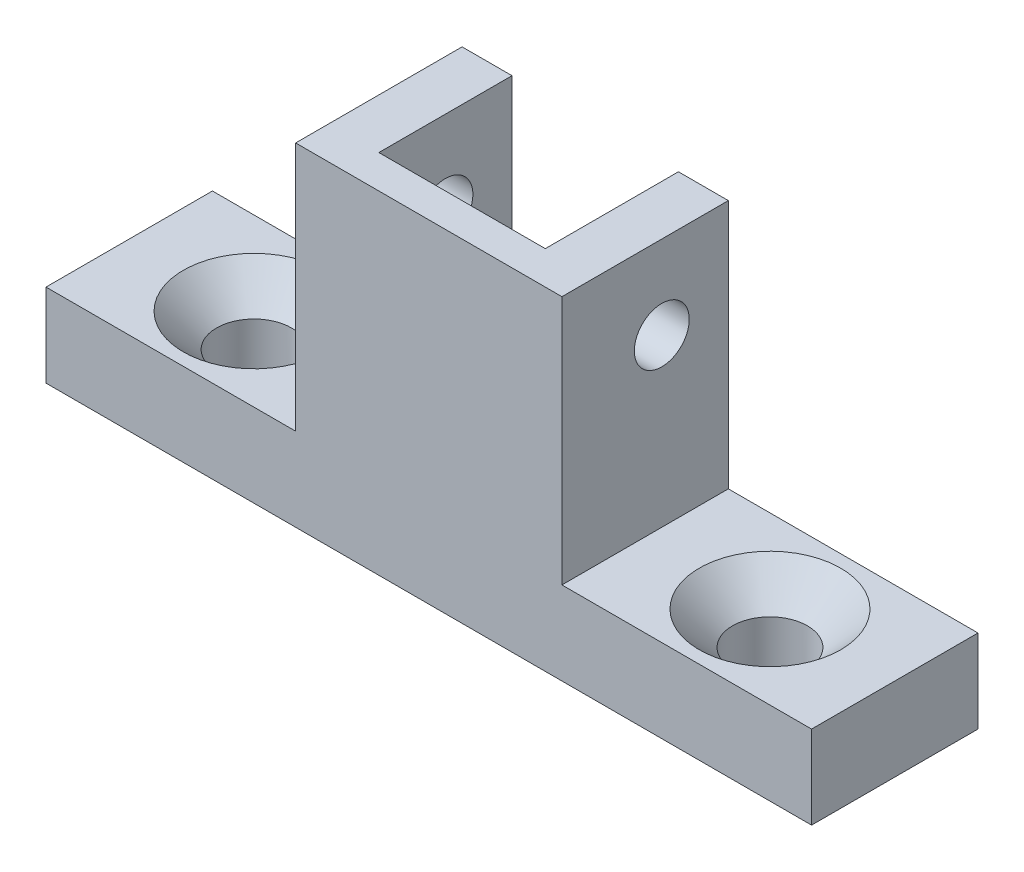
SolidWorks part; units mm, degrees
ref_plane "Front Plane" through (0, 0, 0) normal (0, 0, 1) x (1, 0, 0)
ref_plane "Top Plane" through (0, 0, 0) normal (0, 1, 0) x (1, 0, 0)
ref_plane "Right Plane" through (0, 0, 0) normal (1, 0, 0) x (0, 0, -1)
sketch "Sketch1" plane through (0, 0, 0) normal (0, 0, 1) x (1, 0, 0)
  line L0 (-23, -15) -> (23, -15)
  line L1 (23, -15) -> (23, -10)
  line L2 (23, -10) -> (8, -10)
  line L3 (8, -10) -> (8, 5)
  line L4 (8, 5) -> (-8, 5)
  line L5 (-8, 5) -> (-8, -10)
  line L6 (-8, -10) -> (-23, -10)
  line L7 (-23, -10) -> (-23, -15)
  point P0 (0, -15)
  point P2 (0, 0)
  point P10 (-34.0227, -5.1477)
  point P12 (8, -8.4886)
  dimension "D1" = 5
  dimension "D2" = 15
  dimension "D3" = 16
  dimension "D4" = 10
  dimension "D5" = 5
extrude "Boss-Extrude1" add sketch "Sketch1" along normal mid plane 10
sketch "Sketch2" plane through (0, -10, 0) normal (0, 1, 0) x (1, 0, 0)
  line L0 (-23, 5) -> (-8, -5) construction
  line L1 (8, -5) -> (23, 5) construction
  circle A0 centre (-15.5, 0) radius 2.25
  circle A1 centre (15.5, 0) radius 2.25
  dimension "D1" = 4.5
extrude "Cut-Extrude1" cut sketch "Sketch2" against normal through all
chamfer "Chamfer1" distance 2 angle 45 2 edges at (13.25, -10, 0) (-17.75, -10, 0)
sketch "Sketch4" plane through (0, 5, 0) normal (0, 1, 0) x (1, 0, 0)
  line L0 (8, 5) -> (-8, 5) construction
  line L1 (5, 5) -> (-5, 5)
  line L2 (5, 5) -> (5, -3)
  line L3 (5, -3) -> (-5, -3)
  line L4 (-5, 5) -> (-5, -3)
  line L5 (8, -5) -> (8, 5) construction
  line L6 (8, -5) -> (-8, -5) construction
  point P4 (0, 0)
  point P7 (0, -3)
  dimension "D1" = 3
  dimension "D2" = 2
extrude "Cut-Extrude3" cut sketch "Sketch4" against normal up to surface (15 mm away) up to face at (-11.25, -10, 0)
sketch "Sketch3" plane through (8, 0, 0) normal (1, 0, 0) x (0, 0, -1)
  line L0 (5, 5) -> (-3, 5) construction
  circle A0 centre (1, 0) radius 1.65
  point P3 (1.6941, 0)
  point P4 (0, 0)
  point P9 (1, 5)
  dimension "D1" = 3.3
extrude "Cut-Extrude2" cut sketch "Sketch3" against normal through all
